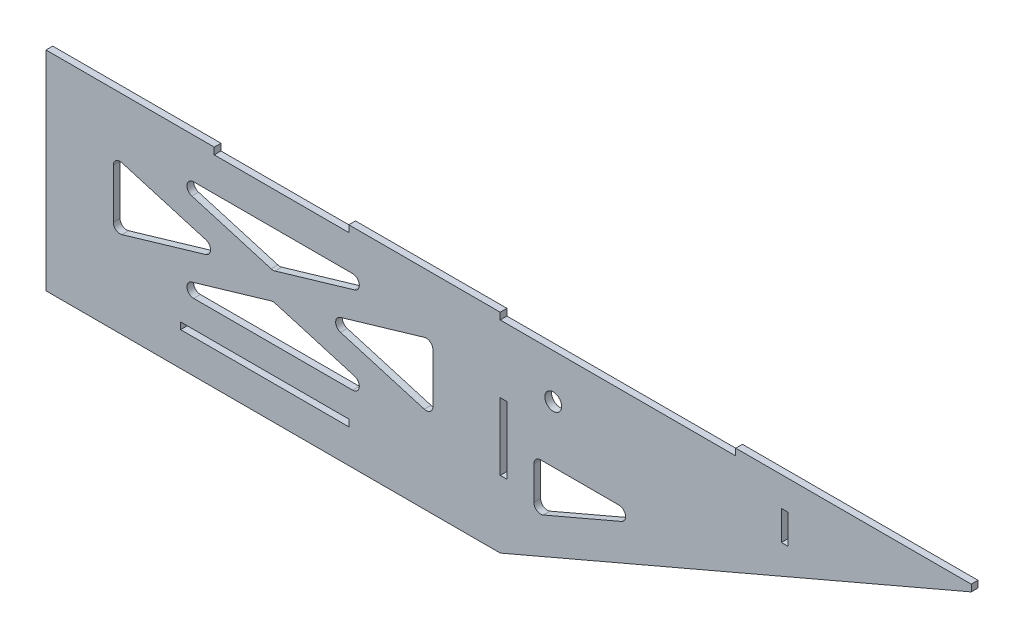
SolidWorks part; units mm, degrees
ref_plane "前视基准面" through (0, 0, 0) normal (0, 0, 1) x (1, 0, 0)
ref_plane "上视基准面" through (0, 0, 0) normal (0, 1, 0) x (1, 0, 0)
ref_plane "右视基准面" through (0, 0, 0) normal (1, 0, 0) x (0, 0, -1)
sketch "草图1" plane through (0, 0, 0) normal (0, 0, 1) x (1, 0, 0)
  line L4 (0, 30) -> (0, -30)
  line L5 (0, 30) -> (135, 30)
  line L6 (0, -30) -> (135, -30)
  line L7 (135, 30) -> (135, -30)
  line L8 (135, 30) -> (275, 30)
  line L9 (275, 30) -> (135, -30)
  line L10 (150.7605, 16.8689) -> (218.5657, 16.8689)
  line L11 (218.5657, 16.8689) -> (218.5657, 23.2879)
  line L12 (147.7878, -13.8052) -> (171.044, -3.8383)
  line L13 (145, -2) -> (145, -11.9669)
  line L14 (147, 0) -> (170.2562, 0)
  line L15 (218.5657, 16.8689) -> (218.5657, 14.5089)
  line L16 (40, -18) -> (40, -20)
  line L17 (40, -18) -> (90, -18)
  line L18 (40, -20) -> (90, -20)
  line L19 (90, -18) -> (90, -20)
  line L20 (20, 12.3271) -> (20, -2.3271)
  line L21 (43.888, 20) -> (91.112, 20)
  line L22 (43.888, -10) -> (91.112, -10)
  line L23 (115, 12.3271) -> (115, -2.3271)
  line L24 (87.5237, 3.0813) -> (112.4357, -4.2458)
  line L25 (47.4763, 3.0813) -> (22.5643, -4.2458)
  line L26 (22.5643, 14.2458) -> (47.4763, 6.9187)
  line L27 (87.5237, 6.9187) -> (112.4357, 14.2458)
  line L28 (43.3237, 16.0813) -> (66.9357, 9.1366)
  line L29 (91.6763, 16.0813) -> (68.0643, 9.1366)
  line L30 (43.3237, -6.0813) -> (66.9357, 0.8634)
  line L31 (91.6763, -6.0813) -> (68.0643, 0.8634)
  line L32 (135, 10) -> (135, -10)
  line L33 (135, 10) -> (137, 10)
  line L34 (135, -10) -> (137, -10)
  line L35 (137, 10) -> (137, -10)
  line L36 (0, 32) -> (0, 30)
  line L37 (0, 32) -> (50, 32)
  line L38 (0, 30) -> (50, 30)
  line L39 (50, 32) -> (50, 30)
  line L40 (90, 32) -> (90, 30)
  line L41 (90, 32) -> (135, 32)
  line L42 (90, 30) -> (135, 30)
  line L43 (135, 32) -> (135, 30)
  line L44 (205, 32) -> (205, 30)
  line L45 (205, 32) -> (275, 32)
  line L46 (205, 30) -> (275, 30)
  line L47 (275, 32) -> (275, 30)
  line L48 (218.5657, 23.2879) -> (220.5657, 23.2879)
  line L49 (220.5657, 23.2879) -> (220.5657, 14.5089)
  line L50 (220.5657, 14.5089) -> (218.5657, 14.5089)
  arc A0 (147, 0) -> (145, -2) centre (147, -2) ccw
  arc A1 (171.044, -3.8383) -> (170.2562, 0) centre (170.2562, -2) ccw
  arc A2 (147.7878, -13.8052) -> (145, -11.9669) centre (147, -11.9669) cw
  circle A3 centre (150.7605, 16.8689) radius 2.5
  arc A5 (22.5643, 14.2458) -> (20, 12.3271) centre (22, 12.3271) ccw
  arc A6 (47.4763, 6.9187) -> (47.4763, 3.0813) centre (46.912, 5) cw
  arc A7 (22.5643, -4.2458) -> (20, -2.3271) centre (22, -2.3271) cw
  arc A8 (112.4357, -4.2458) -> (115, -2.3271) centre (113, -2.3271) ccw
  arc A9 (115, 12.3271) -> (112.4357, 14.2458) centre (113, 12.3271) ccw
  arc A10 (87.5237, 3.0813) -> (87.5237, 6.9187) centre (88.088, 5) cw
  arc A11 (43.3237, 16.0813) -> (43.888, 20) centre (43.888, 18) cw
  arc A12 (91.112, 20) -> (91.6763, 16.0813) centre (91.112, 18) cw
  arc A13 (66.9357, 9.1366) -> (68.0643, 9.1366) centre (67.5, 11.0553) ccw
  arc A14 (43.888, -10) -> (43.3237, -6.0813) centre (43.888, -8) cw
  arc A15 (91.6763, -6.0813) -> (91.112, -10) centre (91.112, -8) cw
  arc A16 (68.0643, 0.8634) -> (66.9357, 0.8634) centre (67.5, -1.0553) ccw
  point P0 (275, 30)
  point P7 (145, -15)
  point P8 (145, 0)
  point P14 (145, 0)
  point P20 (145, -15)
  point P32 (30, 20)
  point P37 (105, 20)
  point P38 (20, 15)
  point P39 (20, -5)
  point P40 (115, 15)
  point P41 (115, -5)
  point P42 (105, -10)
  point P47 (30, -10)
  point P80 (0, 32)
  point P81 (50, 32)
  point P82 (90, 32)
  point P83 (135, 32)
  point P84 (205, 32)
  point P85 (275, 32)
  dimension "D1" = 2
  dimension "D2" = 2
  dimension "D3" = 2
  dimension "D6" = 2
  dimension "D7" = 2
  dimension "D8" = 2
  dimension "D9" = 2
  dimension "D10" = 2
  dimension "D11" = 2
  dimension "D12" = 2
  dimension "D13" = 2
  dimension "D14" = 2
  dimension "D15" = 2
  dimension "D16" = 2
  dimension "D17" = 2
extrude "凸台-拉伸1" add sketch "草图1" along normal blind 2
